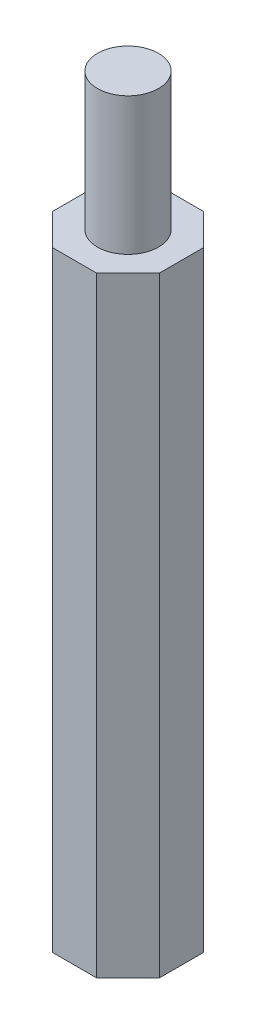
SolidWorks part; units mm, degrees
ref_plane "Plan de face" through (0, 0, 0) normal (0, 0, 1) x (1, 0, 0)
ref_plane "Plan de dessus" through (0, 0, 0) normal (0, 1, 0) x (1, 0, 0)
ref_plane "Plan de droite" through (0, 0, 0) normal (1, 0, 0) x (0, 0, -1)
sketch "Esquisse1" plane through (0, 0, 0) normal (0, 1, 0) x (1, 0, 0)
  line L0 (-1.4497, 3.5) -> (1.4497, 3.5)
  line L1 (1.4497, 3.5) -> (3.5, 1.4497)
  line L2 (3.5, 1.4497) -> (3.5, -1.4497)
  line L3 (3.5, -1.4497) -> (1.4497, -3.5)
  line L4 (1.4497, -3.5) -> (-1.4497, -3.5)
  line L5 (-1.4497, -3.5) -> (-3.5, -1.4497)
  line L6 (-3.5, -1.4497) -> (-3.5, 1.4497)
  line L7 (-3.5, 1.4497) -> (-1.4497, 3.5)
  line L8 (0, 3.5) -> (0, -3.5) construction
  dimension "D1" = 7
extrude "Extrusion1" add sketch "Esquisse1" along normal mid plane 40
sketch "Esquisse2" plane through (0, 20, 0) normal (0, 1, 0) x (1, 0, 0)
  circle A0 centre (0, 0) radius 2
  dimension "D1" = 4
extrude "Extrusion2" add sketch "Esquisse2" along normal blind 9
sketch "Esquisse3" plane through (0, -20, 0) normal (0, -1, 0) x (1, 0, 0)
  circle A0 centre (0, 0) radius 2
  dimension "D1" = 4
extrude "Enlèv. mat.-Extru.1" cut sketch "Esquisse3" against normal blind 9
